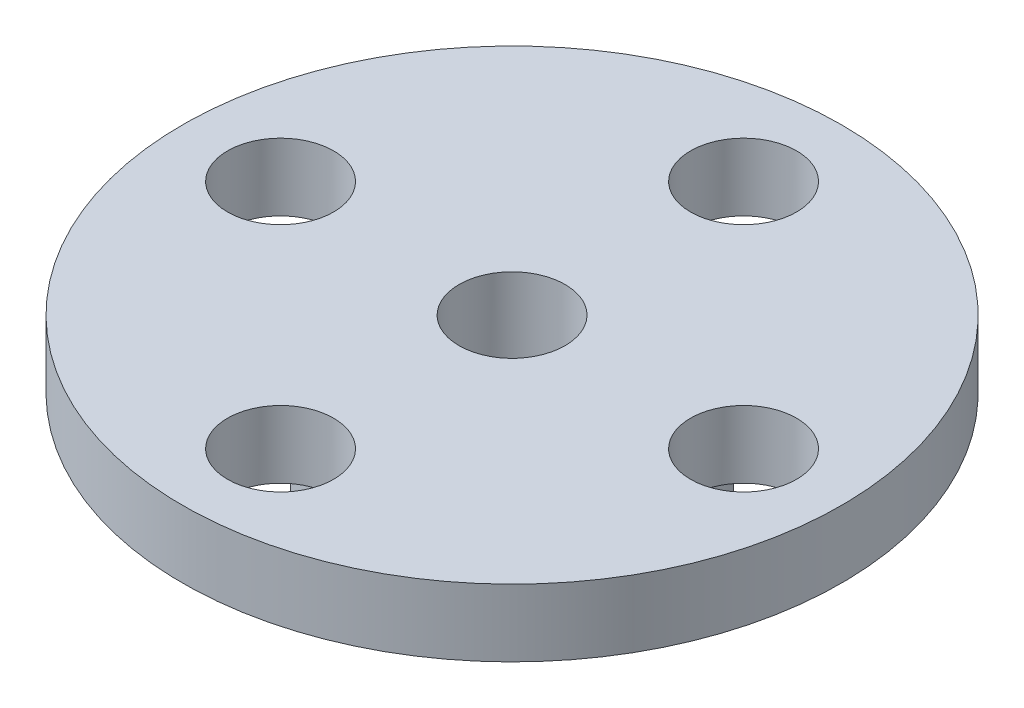
SolidWorks part; units mm, degrees
ref_plane "Front Plane" through (0, 0, 0) normal (0, 0, 1) x (1, 0, 0)
ref_plane "Top Plane" through (0, 0, 0) normal (0, 1, 0) x (1, 0, 0)
ref_plane "Right Plane" through (0, 0, 0) normal (1, 0, 0) x (0, 0, -1)
sketch "Sketch1" plane through (0, 0, 0) normal (1, 0, 0) x (0, 0, -1)
  line L0 (0, 0) -> (0, 5.3848) construction
  line L1 (0, 5.3848) -> (9.9441, 5.3848)
  line L2 (9.9441, 5.3848) -> (9.9441, 3.3528)
  line L3 (9.9441, 3.3528) -> (4.7244, 3.3528)
  line L4 (4.7244, 3.3528) -> (4.7244, 0)
  line L5 (4.7244, 0) -> (0, 0)
  line L6 (0, 0) -> (0, 5.3848)
  dimension "D1" = 2.032
  dimension "D2" = 5.3848
  dimension "D3" = 19.8882
  dimension "D4" = 9.4488
revolve "Revolve1" add sketch "Sketch1" angle 360 about L0
sketch "Sketch2" plane through (0, 5.3848, 0) normal (0, 1, 0) x (1, 0, 0)
  circle A0 centre (0, 0) radius 1.397
  dimension "D1" = 2.794
sketch "Sketch4" plane through (0, 0, 0) normal (0, -1, 0) x (1, 0, 0)
  circle A0 centre (0, 0) radius 2.667
  dimension "D1" = 5.334
extrude "Cut-Extrude2" cut sketch "Sketch4" against normal blind 2.921
sketch "Sketch5" plane through (0, 5.3848, 0) normal (0, 1, 0) x (1, 0, 0)
  circle A0 centre (0, 0) radius 6.985 construction
  circle A1 centre (0, 6.985) radius 1.27
  circle A2 centre (6.985, 0) radius 1.27
  circle A3 centre (0, -6.985) radius 1.27
  circle A4 centre (-6.985, 0) radius 1.27
  dimension "D1" = 13.97
  dimension "D2" = 2.54
  dimension "D3" = 4
hole_wizard "M3 Clearance Hole1" positions "Sketch8" profile "Sketch9" hole size "M3" standard "ANSI Metric" end condition through all
sketch "Sketch8" plane through (0, 5.3848, 0) normal (0, 1, 0) x (1, 0, 0)
  point P0 (-6.985, 0)
  point P3 (0, 0)
  point P6 (6.985, 0)
  point P9 (0, 6.985)
  point P12 (0, -6.985)
sketch "Sketch9" plane through (-6.985, 5.3848, 0) normal (1, 0, 0) x (0, 0, 1)
  line L0 (0, 0) -> (0, 5.3848)
  line L1 (0, 5.3848) -> (1.6, 5.3848)
  line L2 (1.6, 5.3848) -> (1.6, 0)
  line L5 (1.6, 0) -> (0, 0)
  line L11 (0, -6.35) -> (0, 107.95) construction
  dimension "Thru Hole Dia." = 3.2
  dimension "Thru Hole Depth" = 5.3848
